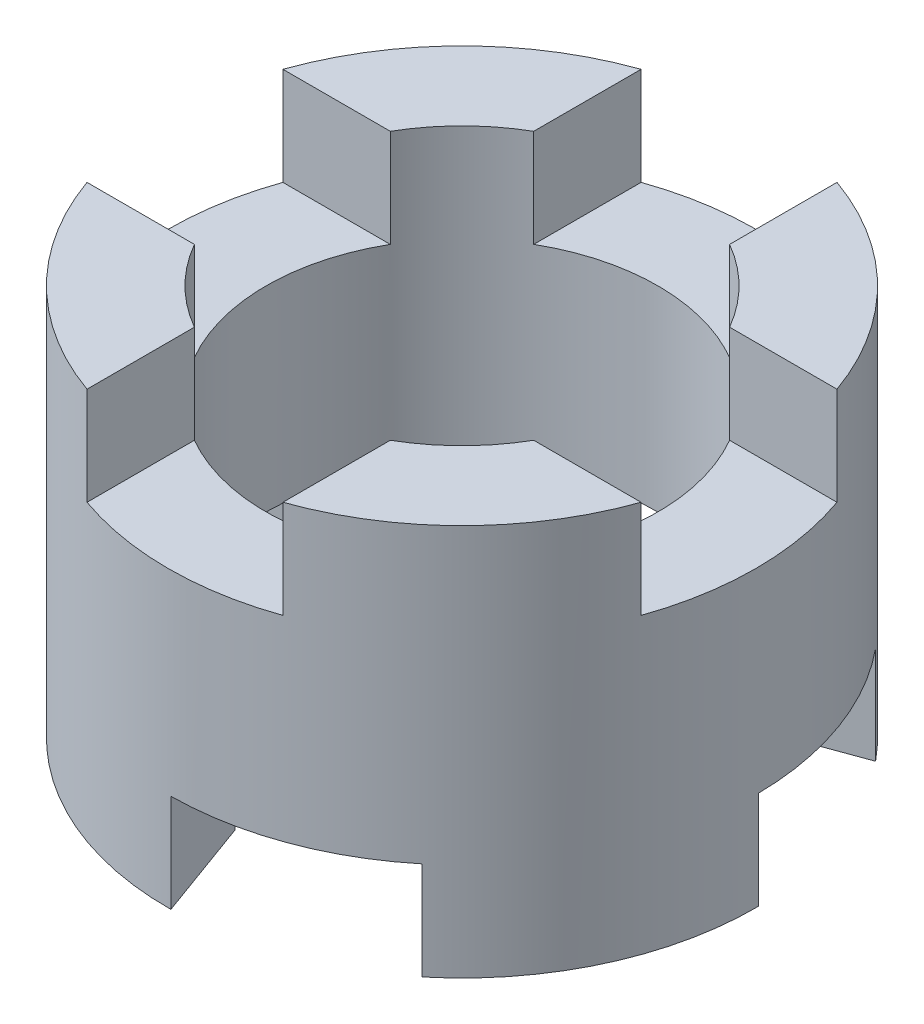
SolidWorks part; units mm, degrees
ref_plane "Front Plane" through (0, 0, 0) normal (0, 0, 1) x (1, 0, 0)
ref_plane "Top Plane" through (0, 0, 0) normal (0, 1, 0) x (1, 0, 0)
ref_plane "Right Plane" through (0, 0, 0) normal (1, 0, 0) x (0, 0, -1)
sketch "Sketch2" plane through (0, 0, 0) normal (0, 1, 0) x (1, 0, 0)
  circle A0 centre (0, 0) radius 19.05
  circle A1 centre (0, 0) radius 12.7
  dimension "D1" = 6.35
  dimension "D2" = 25.4
  dimension "D3" = 38.1
extrude "Boss-Extrude2" add sketch "Sketch2" along normal blind 25.4 contours A0 | A1
sketch "Sketch4" plane through (0, 25.4, 0) normal (0, 1, 0) x (1, 0, 0)
  line L1 (38.1, 6.35) -> (-38.1, 6.35)
  line L2 (38.1, 6.35) -> (38.1, -6.35)
  line L3 (38.1, -6.35) -> (-38.1, -6.35)
  line L4 (-38.1, 6.35) -> (-38.1, -6.35)
  line L5 (0, -6.35) -> (0, 6.35) construction
  line L6 (38.1, 0) -> (-38.1, 0) construction
  point P0 (0, 0)
  dimension "D1" = 12.7
extrude "Cut-Extrude7" cut sketch "Sketch4" against normal blind 6.35
pattern_circular "CirPattern1" count 2 every 90 about axis through (0, 25.4, 0) along (0, 1, 0) of "Cut-Extrude7"
sketch "Sketch8" plane through (0, 0, 0) normal (0, -1, 0) x (1, 0, 0)
  line L0 (-27.7957, 16.8743) -> (32.1394, -4.9402)
  line L1 (-27.7957, 16.8743) -> (-32.1394, 4.9402)
  line L2 (32.1394, -4.9402) -> (27.7957, -16.8743)
  line L3 (-32.1394, 4.9402) -> (27.7957, -16.8743)
  line L4 (-27.7957, 16.8743) -> (27.7957, -16.8743) construction
  line L5 (32.1394, -4.9402) -> (-32.1394, 4.9402) construction
  point P1 (0, 0)
  dimension "D1" = 12.7
extrude "Cut-Extrude9" cut sketch "Sketch8" against normal blind 6.35 contours L3 L2 L0 L1
pattern_circular "CirPattern2" count 2 every 90 about axis through (0, 0, 0) along (0, 1, 0) of "Cut-Extrude9"
equation "\"D1@Sketch4\"=\"D1@Sketch8\""
